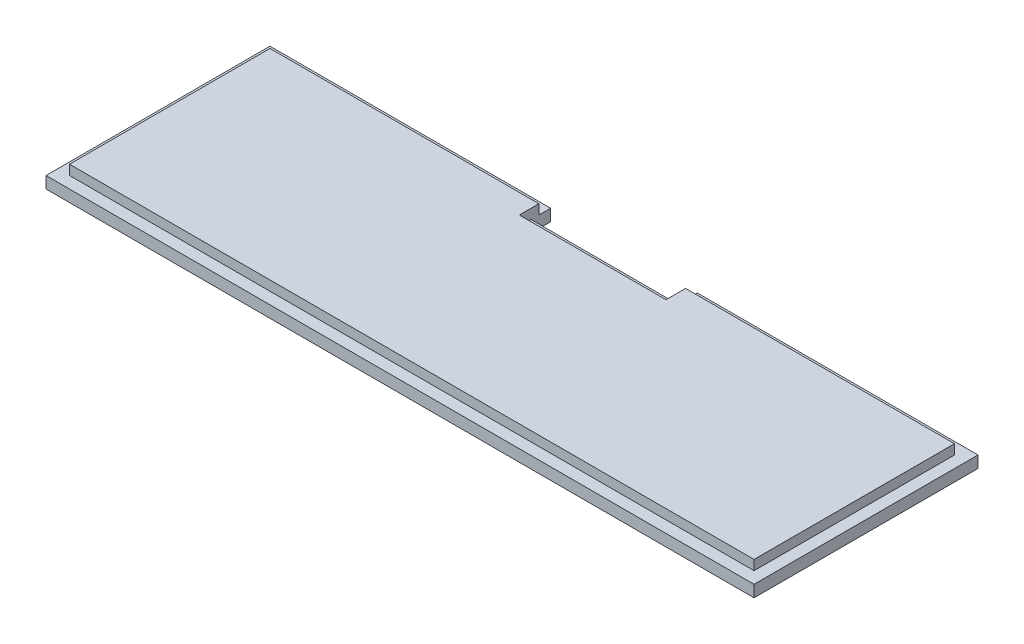
SolidWorks part; units mm, degrees
ref_plane "Přední rovina" through (0, 0, 0) normal (0, 0, 1) x (1, 0, 0)
ref_plane "Horní rovina" through (0, 0, 0) normal (0, 1, 0) x (1, 0, 0)
ref_plane "Pravá rovina" through (0, 0, 0) normal (1, 0, 0) x (0, 0, -1)
sketch "Skica1" plane through (0, 0, 0) normal (0, 1, 0) x (1, 0, 0)
  line L1 (0, 0) -> (72.4, 0)
  line L2 (0, 0) -> (0, 22.9)
  line L3 (0, 22.9) -> (72.4, 22.9)
  line L4 (72.4, 0) -> (72.4, 22.9)
  dimension "D1" = 22.9
  dimension "D2" = 72.4
extrude "Přidat vysunutím2" add sketch "Skica1" along normal blind 1.2
sketch "Skica2" plane through (0, 1.2, 0) normal (0, 1, 0) x (1, 0, 0)
  line L0 (0, 22.9) -> (0, 0) construction
  line L1 (1.2, 21.7) -> (71.2, 21.7)
  line L2 (1.2, 21.7) -> (1.2, 1.2)
  line L3 (1.2, 1.2) -> (71.2, 1.2)
  line L4 (71.2, 21.7) -> (71.2, 1.2)
  line L5 (72.4, 22.9) -> (0, 22.9) construction
  line L6 (72.4, 0) -> (72.4, 22.9) construction
  line L7 (0, 0) -> (72.4, 0) construction
  dimension "D1" = 1.2
  dimension "D2" = 1.2
  dimension "D3" = 1.2
  dimension "D4" = 1.2
extrude "Přidat vysunutím3" add sketch "Skica2" along normal blind 1
sketch "Skica3" plane through (0, 2.2, 0) normal (0, 1, 0) x (1, 0, 0)
  line L0 (72.4, 22.9) -> (0, 22.9) construction
  line L1 (0, 22.9) -> (0, 0) construction
  line L2 (28.7, 22.9) -> (43.7, 22.9)
  line L3 (28.7, 22.9) -> (28.7, 20.9)
  line L4 (28.7, 20.9) -> (43.7, 20.9)
  line L5 (43.7, 22.9) -> (43.7, 20.9)
  dimension "D1" = 2
  dimension "D2" = 15
  dimension "D3" = 28.7
extrude "Odebrat vysunutím1" cut sketch "Skica3" against normal blind 10
sketch "Skica4" plane through (0, 2.2, 0) normal (0, 1, 0) x (1, 0, 0)
  line L1 (28.7, 20.9) -> (43.7, 20.9)
  line L2 (28.7, 20.9) -> (28.7, 19.7)
  line L3 (28.7, 19.7) -> (43.7, 19.7)
  line L4 (43.7, 20.9) -> (43.7, 19.7)
  dimension "D1" = 1.2
  dimension "D2" = 15
extrude "Odebrat vysunutím2" cut sketch "Skica4" against normal blind 1
